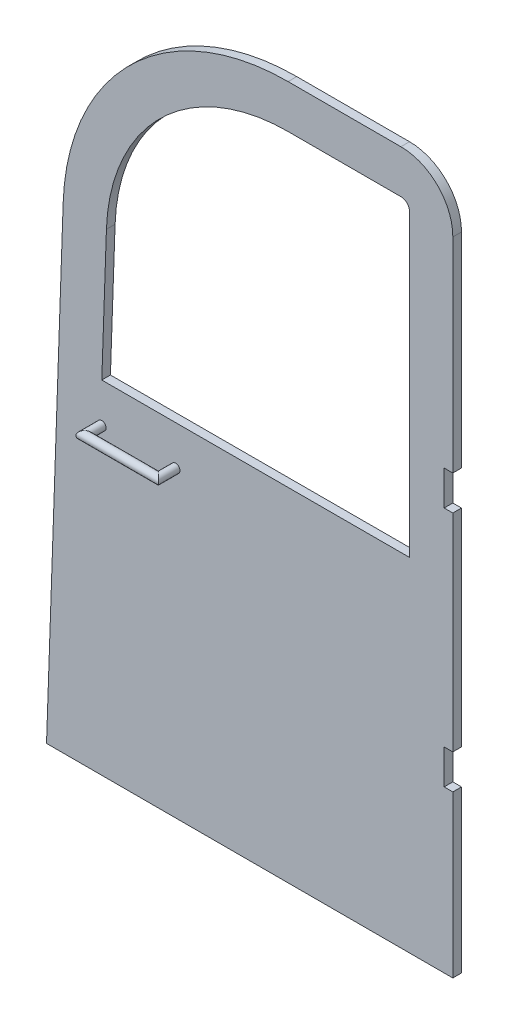
SolidWorks part; units mm, degrees
ref_plane "Front Plane" through (0, 0, 0) normal (0, 0, 1) x (1, 0, 0)
ref_plane "Top Plane" through (0, 0, 0) normal (0, 1, 0) x (1, 0, 0)
ref_plane "Right Plane" through (0, 0, 0) normal (1, 0, 0) x (0, 0, -1)
sketch "Sketch1" plane through (0, 0, 0) normal (0, 0, 1) x (1, 0, 0)
  line L0 (-318.402, 0) -> (873.874, 0)
  line L1 (873.874, 0) -> (873.874, 1883.156)
  line L2 (-318.402, 0) -> (-269.5467, 1399.032)
  line L3 (721.4766, 2036.4458) -> (390.5146, 2036.4458)
  line L4 (-156.2429, 1004.6079) -> (-142.6241, 1394.5998)
  line L5 (721.4766, 1909.4458) -> (390.5146, 1909.4458)
  line L6 (746.874, 1005.3413) -> (746.874, 1883.6826)
  line L8 (-156.2429, 1004.6079) -> (746.874, 1005.3413)
  line L9 (-186.8896, 127) -> (-142.6241, 1394.5998) construction
  line L10 (746.874, 127) -> (746.874, 1883.6826) construction
  line L11 (-186.8896, 127) -> (746.874, 127) construction
  arc A0 (873.874, 1883.156) -> (721.4766, 2036.4458) centre (721.4766, 1884.0458) ccw
  arc A1 (-269.5467, 1399.032) -> (390.5146, 2036.4458) centre (390.5146, 1375.9822) cw
  arc A2 (-142.6241, 1394.5998) -> (390.5146, 1909.4458) centre (390.5146, 1375.9822) cw
  arc A3 (746.874, 1883.6826) -> (721.4766, 1909.4458) centre (721.4766, 1884.0458) ccw
  dimension "D1" = 304.8
  dimension "D7" = 660.4637
  dimension "D2" = 88
  dimension "D3" = 1399.032
  dimension "D4" = 1883.156
  dimension "D5" = 1192.276
  dimension "D6" = 330.962
  dimension "D8" = 127
extrude "Boss-Extrude1" add sketch "Sketch1" along normal blind 25.4
sketch "Sketch2" plane through (0, 0, 25.4) normal (0, 0, 1) x (1, 0, 0)
  line L0 (873.874, 1283.3057) -> (873.874, 1232.5057)
  line L1 (873.874, 0) -> (873.874, 1883.156) construction
  line L2 (873.874, 1232.5057) -> (873.874, 1181.7057)
  line L3 (873.874, 523.7716) -> (873.874, 472.9716)
  line L4 (873.874, 1232.5057) -> (873.874, 1283.3057)
  line L5 (873.874, 1232.5057) -> (873.874, 1181.7057)
  line L6 (873.874, 523.7716) -> (873.874, 574.5716)
  line L7 (873.874, 523.7716) -> (873.874, 472.9716)
  line L8 (873.874, 574.5716) -> (873.874, 523.7716)
  line L10 (873.874, 1283.3057) -> (848.474, 1283.3057)
  line L11 (873.874, 1283.3057) -> (873.874, 1181.7057)
  line L12 (873.874, 1181.7057) -> (848.474, 1181.7057)
  line L13 (848.474, 1283.3057) -> (848.474, 1181.7057)
  line L14 (873.874, 472.9716) -> (848.474, 472.9716)
  line L15 (873.874, 472.9716) -> (873.874, 574.5716)
  line L16 (873.874, 574.5716) -> (848.474, 574.5716)
  line L17 (848.474, 472.9716) -> (848.474, 574.5716)
  line M9 (873.874, 0) -> (873.874, 1883.156)
  dimension "D1" = 50.8
  dimension "D2" = 25.4
  dimension "D3" = 25.4
extrude "Cut-Extrude1" cut sketch "Sketch2" against normal through all contours L10 L13 L12 M9 | L17 L14 L16 M9
ref_plane "Plane1" through (0, 889, 0) normal (0, 1, 0) x (1, 0, 0)
sketch "Sketch5" plane through (0, 889, 0) normal (0, 1, 0) x (1, 0, 0)
  line L0 (-156.2429, -25.4) -> (-156.2429, -76.2)
  line L1 (-156.2429, -76.2) -> (60.484, -76.2)
  line L2 (60.484, -76.2) -> (60.484, -25.4)
  line L3 (-269.5467, -25.4) -> (390.5146, -25.4) construction
  line L4 (-156.2429, 0) -> (-156.2429, 50.8)
  line L5 (-655.7532, 0) -> (655.7532, 0) construction
  line L6 (-156.2429, 50.8) -> (60.484, 50.8)
  line L7 (60.484, 50.8) -> (60.484, 0)
  line L8 (60.484, 0) -> (60.484, -25.4)
  dimension "D1" = 50.8
  dimension "D2" = 216.7268
  dimension "D3" = 50.8
  dimension "D4" = 50.8
sweep "Sweep2" add path "Sketch5" circular profile diameter 25.4 parameters "D3"=25.4
